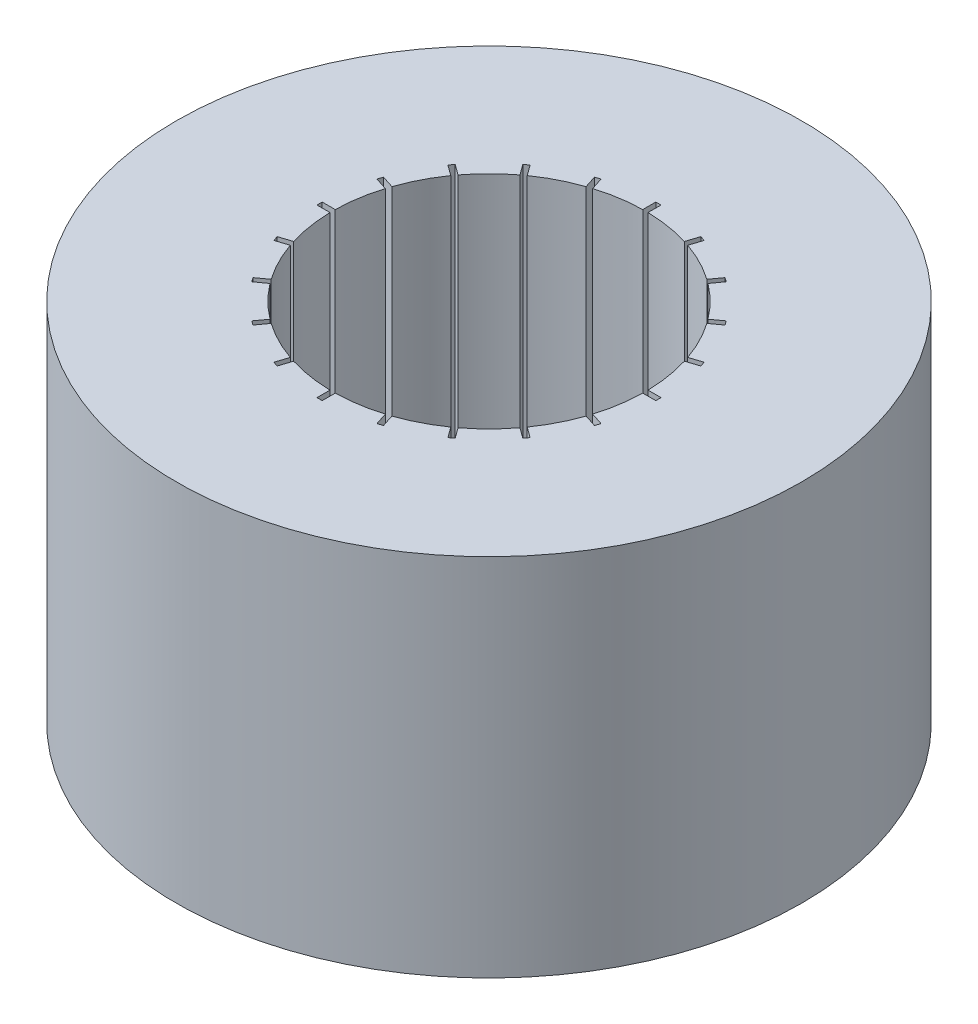
SolidWorks part; units mm, degrees
ref_plane "Front Plane" through (0, 0, 0) normal (0, 0, 1) x (1, 0, 0)
ref_plane "Top Plane" through (0, 0, 0) normal (0, 1, 0) x (1, 0, 0)
ref_plane "Right Plane" through (0, 0, 0) normal (1, 0, 0) x (0, 0, -1)
sketch "Sketch1" plane through (0, 0, 0) normal (0, 1, 0) x (1, 0, 0)
  circle A0 centre (0, 0) radius 762
  dimension "D1" = 1524
extrude "Extrude-Thin1" add sketch "Sketch1" along normal blind 1778 thin
sketch "Sketch2" plane through (0, 1778, 0) normal (0, 1, 0) x (1, 0, 0)
  line L1 (12.7, 825.5) -> (-12.7, 825.5)
  line L2 (12.7, 825.5) -> (12.7, 698.5)
  line L3 (12.7, 698.5) -> (-12.7, 698.5)
  line L4 (-12.7, 825.5) -> (-12.7, 698.5)
  line L5 (12.7, 825.5) -> (-12.7, 698.5) construction
  line L6 (12.7, 698.5) -> (-12.7, 825.5) construction
  circle A0 centre (0, 0) radius 762 construction
  point P0 (0, 762)
  dimension "D1" = 127
  dimension "D2" = 25.4
extrude "Cut-Extrude1" cut sketch "Sketch2" against normal through all
pattern_circular "CirPattern1" count 20 over 360 about axis through (0, 0, 0) along (0, 1, 0) of "Cut-Extrude1"
scale "Scale1" scale about centroid uniform scaling yes scale factor 0.02
